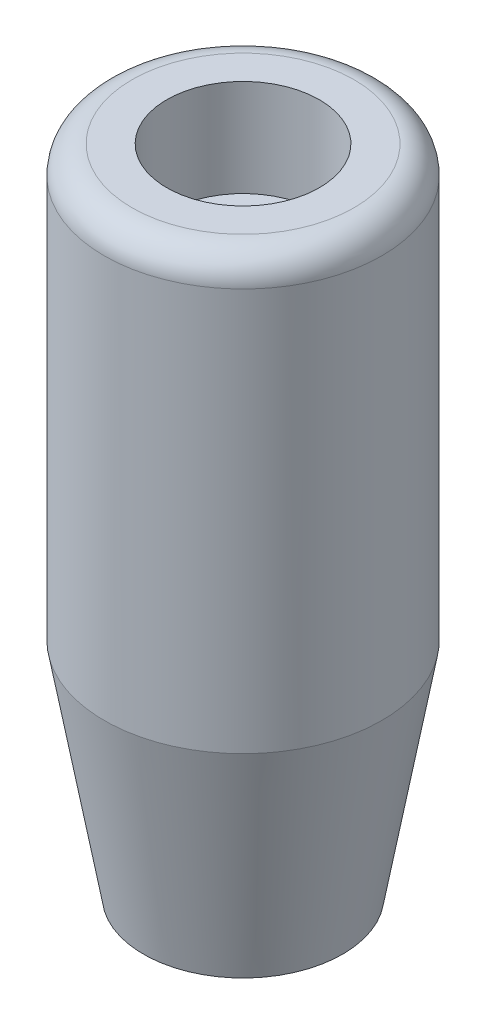
SolidWorks part; units mm, degrees
ref_plane "Plan de face" through (0, 0, 0) normal (0, 0, 1) x (1, 0, 0)
ref_plane "Plan de dessus" through (0, 0, 0) normal (0, 1, 0) x (1, 0, 0)
ref_plane "Plan de droite" through (0, 0, 0) normal (1, 0, 0) x (0, 0, -1)
sketch "Esquisse1" plane through (0, 0, 0) normal (0, 0, 1) x (1, 0, 0)
  line L0 (3.1, 0) -> (3.1, 40)
  line L1 (3.1, 40) -> (5.5, 40)
  line L2 (5.5, 40) -> (5.5, 47)
  line L3 (5.5, 47) -> (10, 47)
  line L4 (10, 47) -> (10, 16)
  line L5 (10, 16) -> (7.1788, 0)
  line L6 (7.1788, 0) -> (3.1, 0)
  line L7 (0, 0) -> (0, 5.0717) construction
  point P10 (3.1, 43.5096)
  point P11 (0, 0)
  dimension "D1" = 47
  dimension "D2" = 6.2
  dimension "D3" = 11
  dimension "D4" = 7
  dimension "D5" = 100
  dimension "D6" = 20
  dimension "D7" = 16
revolve "Révolution1" add sketch "Esquisse1" angle 360 about L7
fillet "Congé1" radius 2 1 edges at (0, 47, -10)
